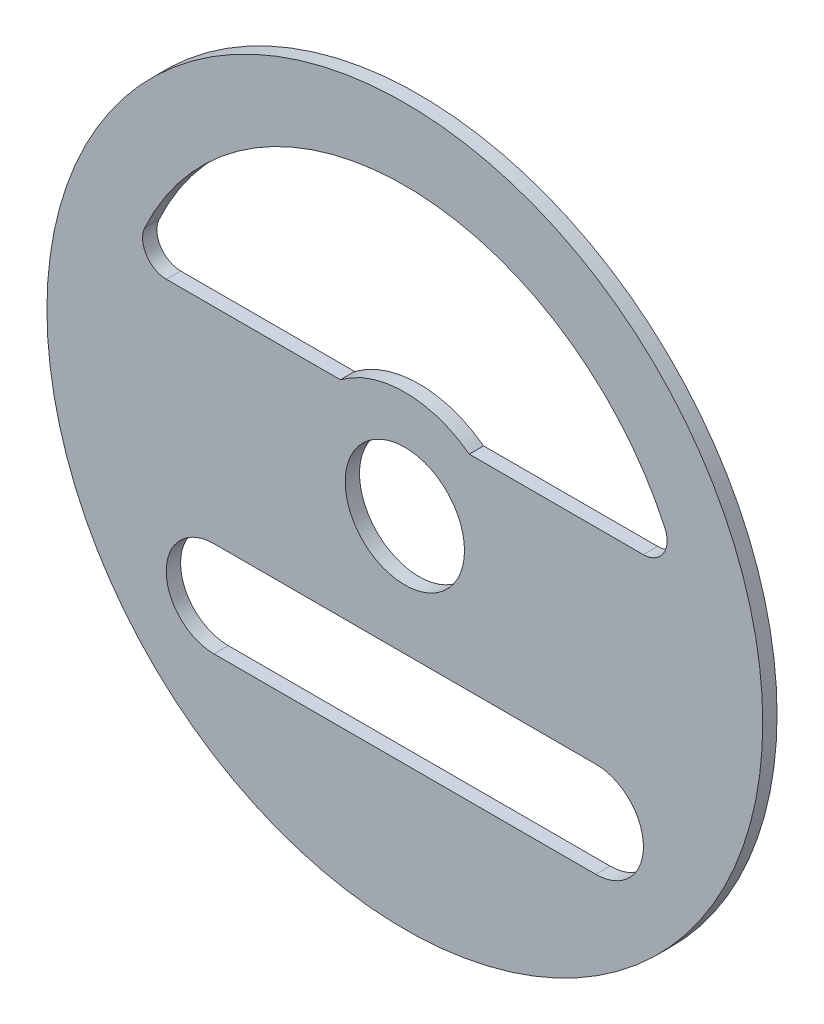
SolidWorks part; units mm, degrees
ref_plane "Front Plane" through (0, 0, 0) normal (0, 0, 1) x (1, 0, 0)
ref_plane "Top Plane" through (0, 0, 0) normal (0, 1, 0) x (1, 0, 0)
ref_plane "Right Plane" through (0, 0, 0) normal (1, 0, 0) x (0, 0, -1)
sketch "Sketch1" plane through (0, 0, 0) normal (0, 0, 1) x (1, 0, 0)
  line L0 (-40, -35) -> (40, -35) construction
  line L1 (-40, -25) -> (40, -25)
  line L2 (-40, -45) -> (40, -45)
  line L3 (0, 0) -> (0, -94.3221) construction
  line L4 (-49.96, 18) -> (-13.5, 18)
  line L5 (13.5, 18) -> (49.96, 18)
  circle A0 centre (0, 0) radius 12.5
  circle A1 centre (0, 0) radius 75
  arc A2 (13.5, 18) -> (-13.5, 18) centre (0, 0) ccw
  arc A3 (-40, -25) -> (-40, -45) centre (-40, -35) ccw
  arc A4 (40, -45) -> (40, -25) centre (40, -35) ccw
  arc A5 (54.5018, 25.0909) -> (-54.5018, 25.0909) centre (0, 0) ccw
  arc A6 (-49.96, 18) -> (-54.5018, 25.0909) centre (-49.96, 23) cw
  arc A7 (49.96, 18) -> (54.5018, 25.0909) centre (49.96, 23) ccw
  point P7 (0, -35)
  dimension "D1" = 25
  dimension "D2" = 150
  dimension "D3" = 45
  dimension "D5" = 10
  dimension "D7" = 120
  dimension "D9" = 5
  dimension "D4" = 80
  dimension "D6" = 35
  dimension "D8" = 18
extrude "Boss-Extrude1" add sketch "Sketch1" along normal blind 3
